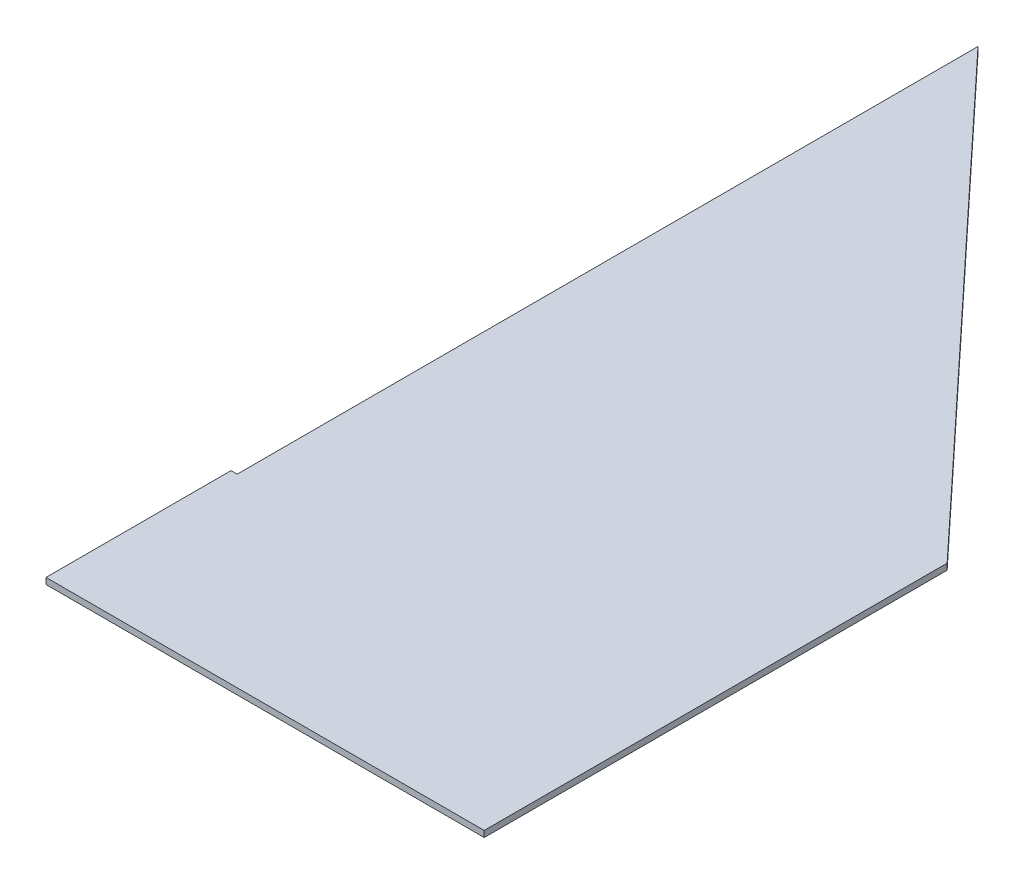
SolidWorks part; units mm, degrees
material "Rohacell 71 IG-F"
ref_plane "Piano frontale" through (0, 0, 0) normal (0, 0, 1) x (1, 0, 0)
ref_plane "Piano superiore" through (0, 0, 0) normal (0, 1, 0) x (1, 0, 0)
ref_plane "Piano destro" through (0, 0, 0) normal (1, 0, 0) x (0, 0, -1)
sketch "Forma aletta" plane through (0, 0, 0) normal (0, 1, 0) x (1, 0, 0)
  line L0 (0, 0) -> (0, 300) construction
  line L1 (0, 300) -> (0, 59.93)
  line L2 (0, 0) -> (140, 0)
  line L3 (140, 0) -> (140, 150)
  line L4 (140, 150) -> (0, 300)
  line L5 (0, 0) -> (-2, 0)
  line L6 (-2, 0) -> (-2, 59.93)
  line L7 (-2, 59.93) -> (0, 59.93)
  line L8 (-146, 59.93) -> (0, 59.93) construction
  line L9 (-146, 59.93) -> (0, 59.93) construction
  dimension "D1" = 300
  dimension "D2" = 2
  dimension "D3" = 205.1828
  dimension "D6" = 140
extrude "Estrusione-Estrusione1" add sketch "Forma aletta" along normal blind 2
